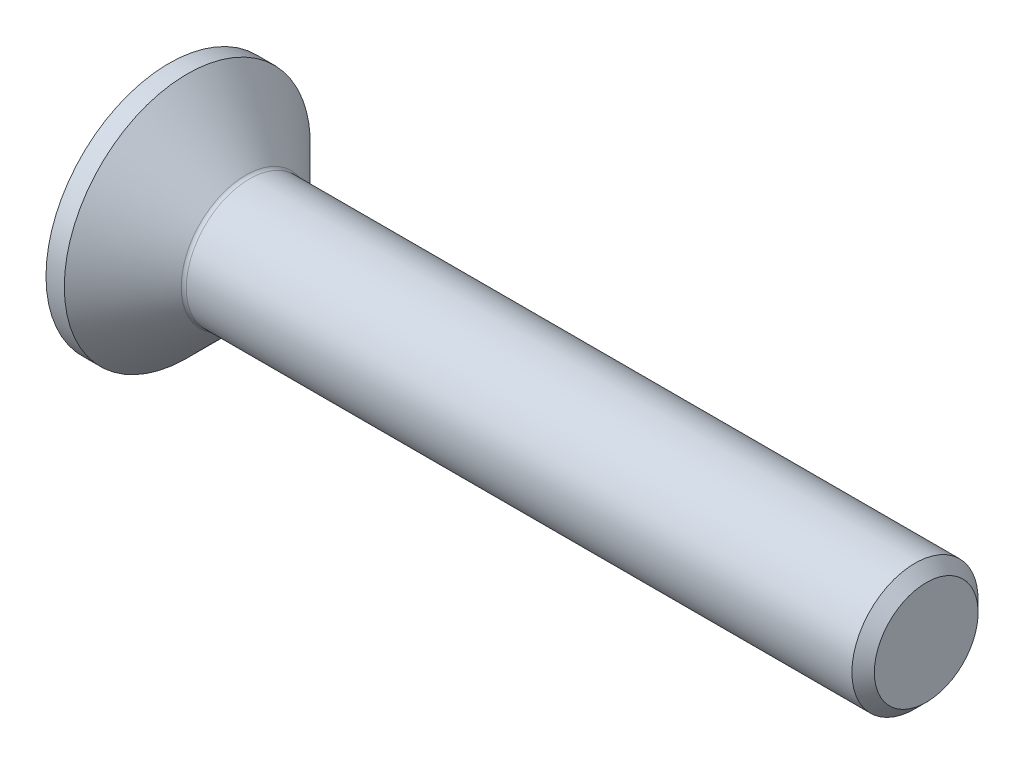
SolidWorks part; units mm, degrees
ref_plane "Plane1" through (0, 0, 0) normal (0, 0, 1) x (1, 0, 0)
ref_plane "Plane2" through (0, 0, 0) normal (0, 1, 0) x (1, 0, 0)
ref_plane "Plane3" through (0, 0, 0) normal (1, 0, 0) x (0, 0, -1)
sketch "BodySke" plane through (0, 0, 0) normal (0, 0, 1) x (1, 0, 0)
  line L0 (0, 0) -> (0, 4.875)
  line L1 (0.725, 4.875) -> (3.1, 2.5)
  line L2 (0, 4.875) -> (0.725, 4.875)
  line L3 (3.1, 2.5) -> (29.555, 2.5)
  line L4 (30, 2.055) -> (30, 0)
  line L5 (30, 0) -> (0, 0)
  line L6 (0, 0) -> (127, 0) construction
  line L7 (0.725, -4.875) -> (3.1, -2.5) construction
  line L8 (30, 2.055) -> (29.555, 2.5)
  line L9 (0, -4.875) -> (0.725, -4.875) construction
  line L10 (30, -2.055) -> (29.555, -2.5) construction
  line L11 (3.9, 8.85) -> (3.9, -13.375) construction
  line L12 (0, 19.05) -> (0, -3.175) construction
  dimension "D1" = 0.725
  dimension "Diameter" = 5
  dimension "Head_ht" = 3.1
  dimension "Length" = 30
  dimension "Body_ch_ang" = 45
  dimension "Head_dia" = 9.75
  dimension "Minor_dia" = 4.11
  dimension "Head_ang" = 90
  dimension "Advance" = 0.8
  dimension "Thread_nom" = 30
revolve "BaseBody" add sketch "BodySke" angle 360 about L6
cosmetic thread "ThreadCosmetic" [suppressed] parameters "Thread_length"=25.3, "Thread_minor"=4.11
fillet "Fillet1" radius 0.2 1 edges at (3.1, 0, 2.5)
sketch "Sketch2" plane through (0, 0, 0) normal (0, 0, 1) x (1, 0, 0)
  line L0 (0, 1.5) -> (1.9, 1.5)
  line L1 (1.9, 1.5) -> (2.766, 0)
  line L2 (0, 0) -> (127, 0) construction
  line L3 (2.766, 0) -> (0, 0)
  line L4 (0, 0) -> (0, 1.5)
  line L5 (0, -1.5) -> (1.9, -1.5) construction
  line L6 (0, 0) -> (47.625, 0) construction
  line L8 (0, 4.875) -> (0, -4.875) construction
  dimension "D2" = 60
  dimension "PreBroach_depth" = 1.9
  dimension "PreBroach_dia" = 3
revolve "PreBroach" cut sketch "Sketch2" angle 360 about L6
sketch "Sketch3" plane through (0, 0, 0) normal (-1, 0, 0) x (0, 0, 1)
  line L0 (-1.5, -0.866) -> (-1.5, 0.866)
  line L1 (-1.5, 0.866) -> (0, 1.7321)
  line L2 (0, 1.7321) -> (1.5, 0.866)
  line L3 (1.5, 0.866) -> (1.5, -0.866)
  line L4 (1.5, -0.866) -> (0, -1.7321)
  line L5 (0, -1.7321) -> (-1.5, -0.866)
  dimension "D1" = 1.5
  dimension "D2" = 1.5
  dimension "D3" = 3
  dimension "Hex_size" = 3
extrude "Hex" cut sketch "Sketch3" against normal blind 1.9
sketch "ThdSchSke" plane through (0, 0, 0) normal (0, 0, 1) x (1, 0, 0)
  line L0 (4.7, -2.055) -> (4.3884, -2.5)
  line L1 (4.7, -2.055) -> (5.0116, -2.5)
  line L2 (5.0116, -2.5) -> (5.0116, -3.125)
  line L3 (-3.175, 0) -> (5.1513, 0) construction
  line L4 (0, 4.875) -> (0, -4.875) construction
  line L5 (5.0116, -3.125) -> (4.3884, -3.125)
  line L6 (4.3884, -3.125) -> (4.3884, -2.5)
  dimension "Thread_minor" = 4.11
  dimension "Diameter" = 5
  dimension "Start" = 4.7
  dimension "SideAngle" = 55
  dimension "VeeAngle" = 70
  dimension "Overcut" = 6.25
revolve "ThreadSchematic" [suppressed] cut sketch "ThdSchSke" angle 360 about L3
pattern_linear "ThdSchPat" [suppressed]
equation "\"Thread_minor@ThreadCosmetic\"  =  \"Minor_dia@BodySke\""
equation "\"D1@Sketch3\" = \"Hex_size@Sketch3\" / 2"
equation "\"D2@Sketch3\" = \"D1@Sketch3\""
equation "\"D3@Sketch3\" = \"Hex_size@Sketch3\""
equation "\"Thread_length@ThreadCosmetic\" = ((sgn( (\"Length@BodySke\" - \"Advance@BodySke\" * 2.0 - \"Head_ht@BodySke\" ) - \"Thread_nom@BodySke\" )-1)*( (\"Length@BodySke\" - \"Advance@BodySke\" * 2.0 - \"Head_ht@BodySke\" ) - \"Thread_nom@BodySke\" ))/-2+ \"Thread_nom@BodySke\""
equation "\"Thread_minor@ThdSchSke\" = \"Minor_dia@BodySke\""
equation "\"Diameter@ThdSchSke\" = \"Diameter@BodySke\""
equation "\"Overcut@ThdSchSke\" = \"Diameter@BodySke\" * 1.25"
equation "\"Start@ThdSchSke\" = 0.000001 + \"Length@BodySke\" - \"Thread_length@ThreadCosmetic\"  '---Countersunk---"
equation "\"Num_threads@ThdSchPat\" = int( \"Thread_length@ThreadCosmetic\" / \"Advance@BodySke\" + 0.999 )  + 1"
equation "\"Advance@ThdSchPat\" = \"Thread_length@ThreadCosmetic\" /  (\"Num_threads@ThdSchPat\" - 1) 'relax it"
equation "\"Num_threads@ThdSchPat\" = \"Num_threads@ThdSchPat\" - sgn( \"Num_threads@ThdSchPat\" - 1) '---chamfered tips only---"
